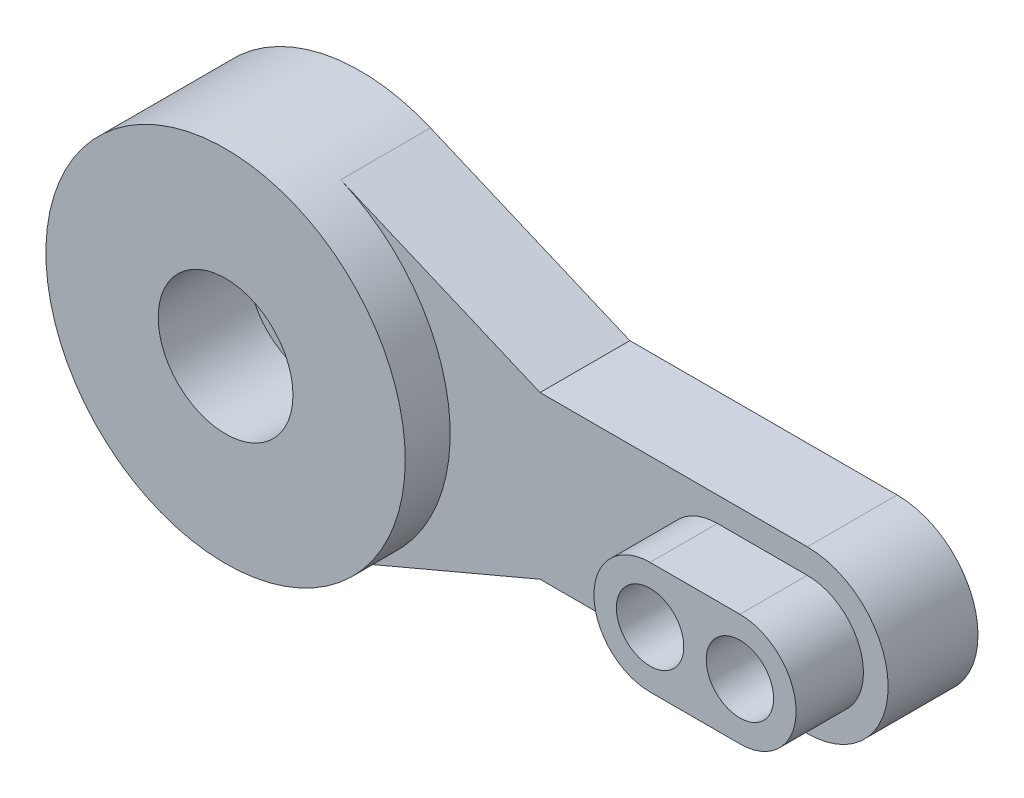
SolidWorks part; units mm, degrees
ref_plane "Top Plane" through (0, 0, 0) normal (0, 0, 1) x (1, 0, 0)
ref_plane "Right Plane" through (0, 0, 0) normal (0, 1, 0) x (1, 0, 0)
ref_plane "Front Plane" through (0, 0, 0) normal (1, 0, 0) x (0, 0, -1)
sketch "Sketch1" plane through (0, 0, 0) normal (0, 0, 1) x (1, 0, 0)
  line L0 (0, 0) -> (23.9, 0) construction
  line L1 (3.1239, 7.3649) -> (12, 3.6)
  line L2 (12, 3.6) -> (23.9, 3.6)
  line L3 (12, -3.6) -> (23.9, -3.6)
  line L4 (3.1239, -7.3649) -> (12, -3.6)
  circle A0 centre (0, 0) radius 3 construction
  circle A1 centre (23.9, 0) radius 1.5 construction
  circle A2 centre (19.9, 0) radius 1.5 construction
  arc A3 (3.1239, 7.3649) -> (3.1239, -7.3649) centre (0, 0) ccw
  arc A4 (23.9, -3.6) -> (23.9, 3.6) centre (23.9, 0) ccw
  point P17 (-8, 0)
  point P18 (27.5, 0)
  dimension "D1" = 23.9
  dimension "D2" = 3
  dimension "D3" = 3
  dimension "D5" = 6
  dimension "D6" = 16
  dimension "D7" = 35.5
  dimension "D4" = 19.9
  dimension "D8" = 12
extrude "Boss-Extrude1" add sketch "Sketch1" along normal blind 4
sketch "Sketch4" plane through (0, 0, 4) normal (0, 0, 1) x (1, 0, 0)
  circle A0 centre (0, 0) radius 8
  arc A1 (3.1239, 7.3649) -> (3.1239, -7.3649) centre (0, 0) ccw construction
extrude "Boss-Extrude2" add sketch "Sketch4" along normal blind 2
sketch "Sketch5" plane through (0, 0, 4) normal (0, 0, 1) x (1, 0, 0)
  line L0 (23.9, 0) -> (19.9, 0) construction
  line L1 (0, 0) -> (23.9, 0) construction
  line L2 (23.9, -2.5) -> (19.9, -2.5)
  line L3 (23.9, 2.5) -> (19.9, 2.5)
  arc A0 (23.9, -2.5) -> (23.9, 2.5) centre (23.9, 0) ccw
  arc A1 (19.9, 2.5) -> (19.9, -2.5) centre (19.9, 0) ccw
  point P5 (21.9, 0)
  dimension "D1" = 5
extrude "Boss-Extrude3" add sketch "Sketch5" along normal blind 3
hole_wizard "Ø3.0 (3) Diameter Hole1" positions "Sketch8" profile "Sketch9" hole size "Ø3.0" standard "ISO" end condition through all
sketch "Sketch8" plane through (0, 0, 0) normal (0, 0, -1) x (-1, 0, 0)
  point P0 (-23.9, 0)
  point P3 (-19.9, 0)
sketch "Sketch9" plane through (23.9, 0, 0) normal (1, 0, 0) x (0, 1, 0)
  line L0 (0, 0) -> (0, 7)
  line L1 (0, 7) -> (1.5, 7)
  line L2 (1.5, 7) -> (1.5, 0)
  line L5 (1.5, 0) -> (0, 0)
  line L11 (0, -6.35) -> (0, 107.95) construction
  dimension "Thru Hole Dia." = 3
  dimension "Thru Hole Depth" = 7
hole_wizard "Ø6.0 (6) Diameter Hole1" positions "Sketch10" profile "Sketch11" hole size "Ø6.0" standard "ISO" end condition through all
sketch "Sketch10" plane through (0, 0, 0) normal (0, 0, -1) x (-1, 0, 0)
  point P0 (0, 0)
sketch "Sketch11" plane through (0, 0, 0) normal (1, 0, 0) x (0, 1, 0)
  line L0 (0, 0) -> (0, 7)
  line L1 (0, 7) -> (3, 7)
  line L2 (3, 7) -> (3, 0)
  line L5 (3, 0) -> (0, 0)
  line L11 (0, -6.35) -> (0, 107.95) construction
  dimension "Thru Hole Dia." = 6
  dimension "Thru Hole Depth" = 7
sketch "Sketch12" plane through (0, 0, 0) normal (0, 0, 1) x (1, 0, 0)
  circle A0 centre (0, 0) radius 2
  circle A1 centre (0, 0) radius 3 construction
  circle A2 centre (0, 0) radius 3
  dimension "D1" = 1
extrude "Boss-Extrude4" add sketch "Sketch12" along normal offset from surface (2 mm away) 4 up to face at (3, 0, 6)
